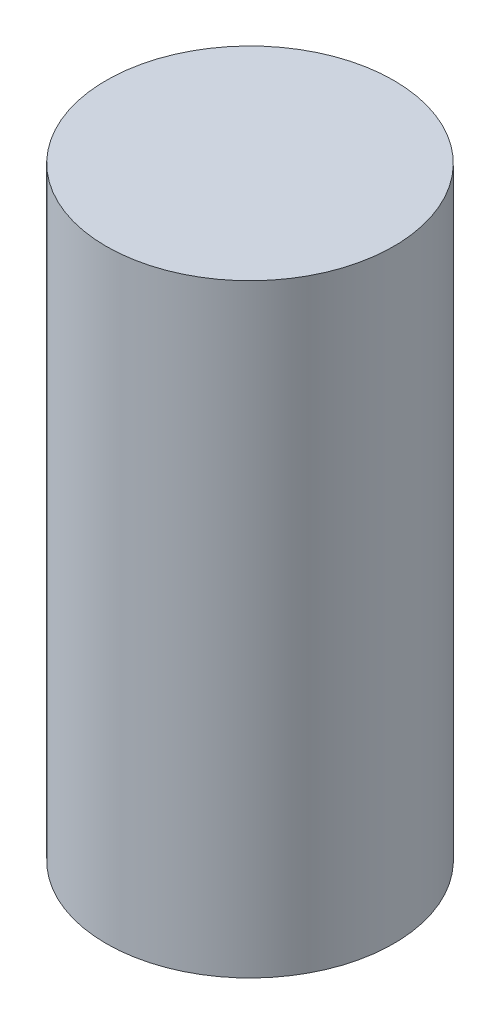
SolidWorks part; units mm, degrees
ref_plane "Front Plane" through (0, 0, 0) normal (0, 0, 1) x (1, 0, 0)
ref_plane "Top Plane" through (0, 0, 0) normal (0, 1, 0) x (1, 0, 0)
ref_plane "Right Plane" through (0, 0, 0) normal (1, 0, 0) x (0, 0, -1)
sketch "Sketch1" plane through (0, 0, 0) normal (0, 1, 0) x (1, 0, 0)
  circle A0 centre (0, 0) radius 50
extrude "Boss-Extrude1" add sketch "Sketch1" along normal blind 210
